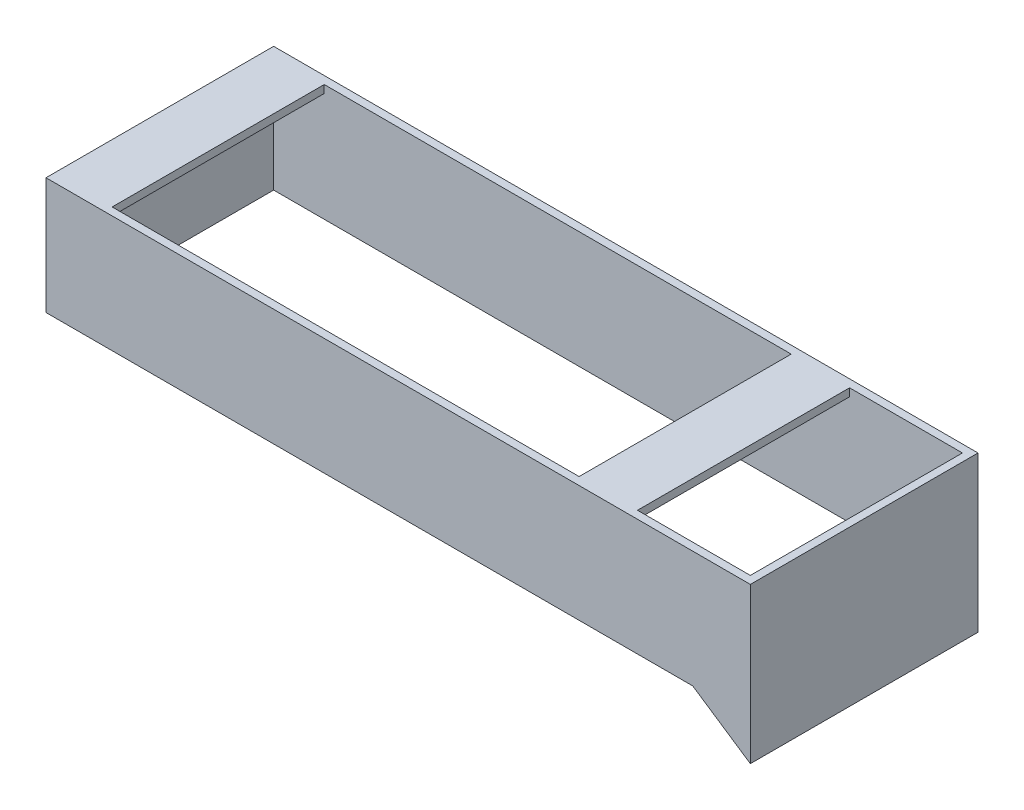
SolidWorks part; units mm, degrees
ref_plane "Спереди" through (0, 0, 0) normal (0, 0, 1) x (1, 0, 0)
ref_plane "Сверху" through (0, 0, 0) normal (0, 1, 0) x (1, 0, 0)
ref_plane "Справа" through (0, 0, 0) normal (1, 0, 0) x (0, 0, -1)
other "Configuration Table"
sketch "Эскиз2" plane through (0, 0, 0) normal (0, 1, 0) x (1, 0, 0)
  line L9 (-90.5, -29.25) -> (90.5, -29.25)
  line L10 (-90.5, -29.25) -> (-90.5, 29.25)
  line L11 (-90.5, 29.25) -> (90.5, 29.25)
  line L12 (90.5, -29.25) -> (90.5, 29.25)
  line L13 (-90.5, -29.25) -> (90.5, 29.25) construction
  line L14 (-90.5, 29.25) -> (90.5, -29.25) construction
  line L15 (-88.5, -27.25) -> (88.5, -27.25)
  line L16 (-88.5, -27.25) -> (-88.5, 27.25)
  line L17 (-88.5, 27.25) -> (88.5, 27.25)
  line L18 (88.5, -27.25) -> (88.5, 27.25)
  line L19 (-88.5, -27.25) -> (88.5, 27.25) construction
  line L20 (-88.5, 27.25) -> (88.5, -27.25) construction
  point P0 (0, 0)
  point P5 (0, 0)
extrude "Бобышка-Вытянуть1" add sketch "Эскиз2" along normal blind 30
sketch "Эскиз3" plane through (0, 0, 0) normal (0, -1, 0) x (1, 0, 0)
  line L0 (90.5, -29.25) -> (-90.5, -29.25) construction
  line L1 (90.5, 29.25) -> (75.7, 29.25)
  line L2 (90.5, 29.25) -> (90.5, -29.25)
  line L3 (90.5, -29.25) -> (75.7, -29.25)
  line L4 (75.7, 29.25) -> (75.7, -29.25)
extrude "Бобышка-Вытянуть2" add sketch "Эскиз3" along normal blind 9.9
sketch "Эскиз5" plane through (0, 0, 0) normal (0, 1, 0) x (1, 0, 0)
  line L1 (75.7, -27.25) -> (88.5, -27.25)
  line L2 (75.7, -27.25) -> (75.7, 27.25)
  line L3 (75.7, 27.25) -> (88.5, 27.25)
  line L4 (88.5, -27.25) -> (88.5, 27.25)
extrude "Вырез-Вытянуть1" cut sketch "Эскиз5" against normal blind 9.9
sketch "Эскиз6" plane through (0, 0, -29.25) normal (0, 0, -1) x (-1, 0, 0)
  line L0 (-90.5, -9.9) -> (-75.7, 0)
  line L1 (-75.7, 0) -> (-75.7, -9.9)
  line L2 (-75.7, -9.9) -> (-90.5, -9.9)
extrude "Вырез-Вытянуть2" cut sketch "Эскиз6" against normal blind 1000
sketch "Эскиз7" plane through (0, 30, 0) normal (0, 1, 0) x (1, 0, 0)
  line L0 (-90.5, -29.25) -> (90.5, -29.25) construction
  line L1 (-90.5, 29.25) -> (-75.5, 29.25)
  line L2 (-90.5, 29.25) -> (-90.5, -29.25)
  line L3 (-90.5, -29.25) -> (-75.5, -29.25)
  line L4 (-75.5, 29.25) -> (-75.5, -29.25)
  line L6 (90.5, 29.25) -> (-90.5, 29.25) construction
  line L8 (59.4977, 29.25) -> (44.4977, 29.25)
  line L9 (59.4977, 29.25) -> (59.4977, -29.25)
  line L10 (59.4977, -29.25) -> (44.4977, -29.25)
  line L11 (44.4977, 29.25) -> (44.4977, -29.25)
  point P10 (0, 0)
  point P14 (0, 0)
  point P15 (0, 0)
extrude "Бобышка-Вытянуть3" add sketch "Эскиз7" against normal blind 2
